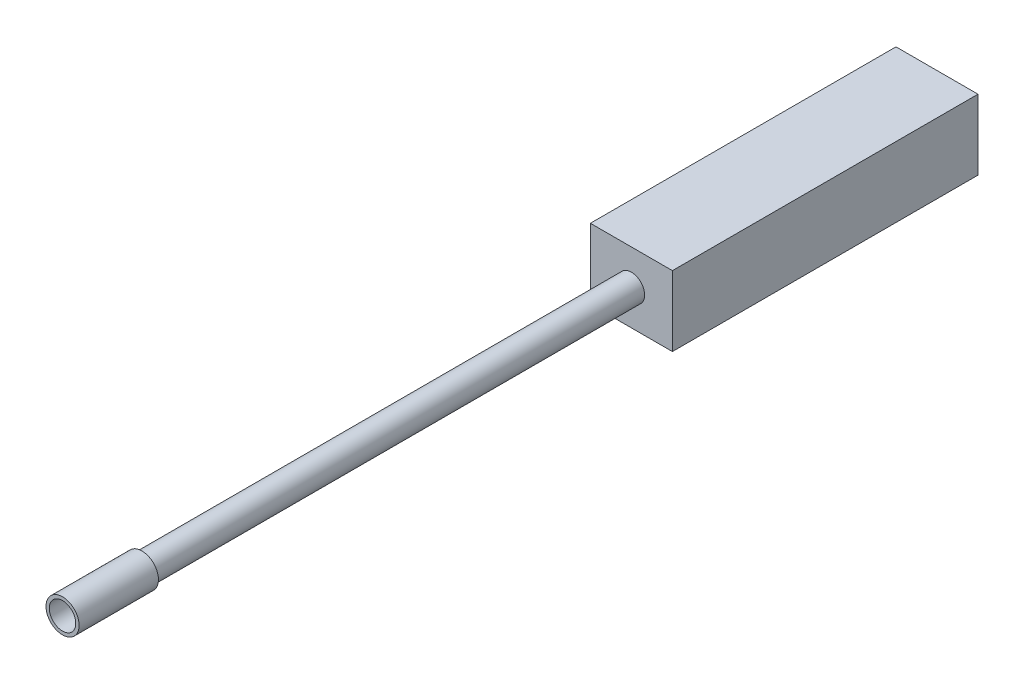
SolidWorks part; units mm, degrees
material "Cast Alloy Steel"
ref_plane "Front" through (0, 0, 0) normal (0, 0, 1) x (1, 0, 0)
ref_plane "Top" through (0, 0, 0) normal (0, 1, 0) x (1, 0, 0)
ref_plane "Right" through (0, 0, 0) normal (1, 0, 0) x (0, 0, -1)
sketch "Sketch1" plane through (0, 0, 0) normal (0, 0, 1) x (1, 0, 0)
  line L1 (0, 0) -> (157.48, 0)
  line L2 (0, 0) -> (0, 134.62)
  line L3 (0, 134.62) -> (157.48, 134.62)
  line L4 (157.48, 0) -> (157.48, 134.62)
  dimension "D1" = 157.48
  dimension "D2" = 134.62
extrude "Boss-Extrude1" add sketch "Sketch1" along normal blind 586.74
sketch "Sketch2" plane through (0, 0, 586.74) normal (0, 0, 1) x (1, 0, 0)
  line L0 (0, 67.31) -> (157.48, 67.31) construction
  line L1 (0, 134.62) -> (0, 0) construction
  line L2 (157.48, 0) -> (157.48, 134.62) construction
  line L3 (78.74, 134.62) -> (78.74, 0) construction
  line L4 (157.48, 134.62) -> (0, 134.62) construction
  line L5 (0, 0) -> (157.48, 0) construction
  circle A0 centre (78.74, 67.31) radius 25.4
  circle A1 centre (78.74, 67.31) radius 6.35
  dimension "D1" = 50.8
  dimension "D2" = 12.7
extrude "Boss-Extrude2" add sketch "Sketch2" along normal blind 1016
sketch "Sketch3" plane through (0, 0, 1602.74) normal (0, 0, 1) x (1, 0, 0)
  circle A0 centre (78.74, 67.31) radius 31.75
  circle A2 centre (78.74, 67.31) radius 25.4 construction
  circle A3 centre (78.74, 67.31) radius 25.4
  dimension "D1" = 63.5
extrude "Boss-Extrude3" add sketch "Sketch3" along normal mid plane 152.4
